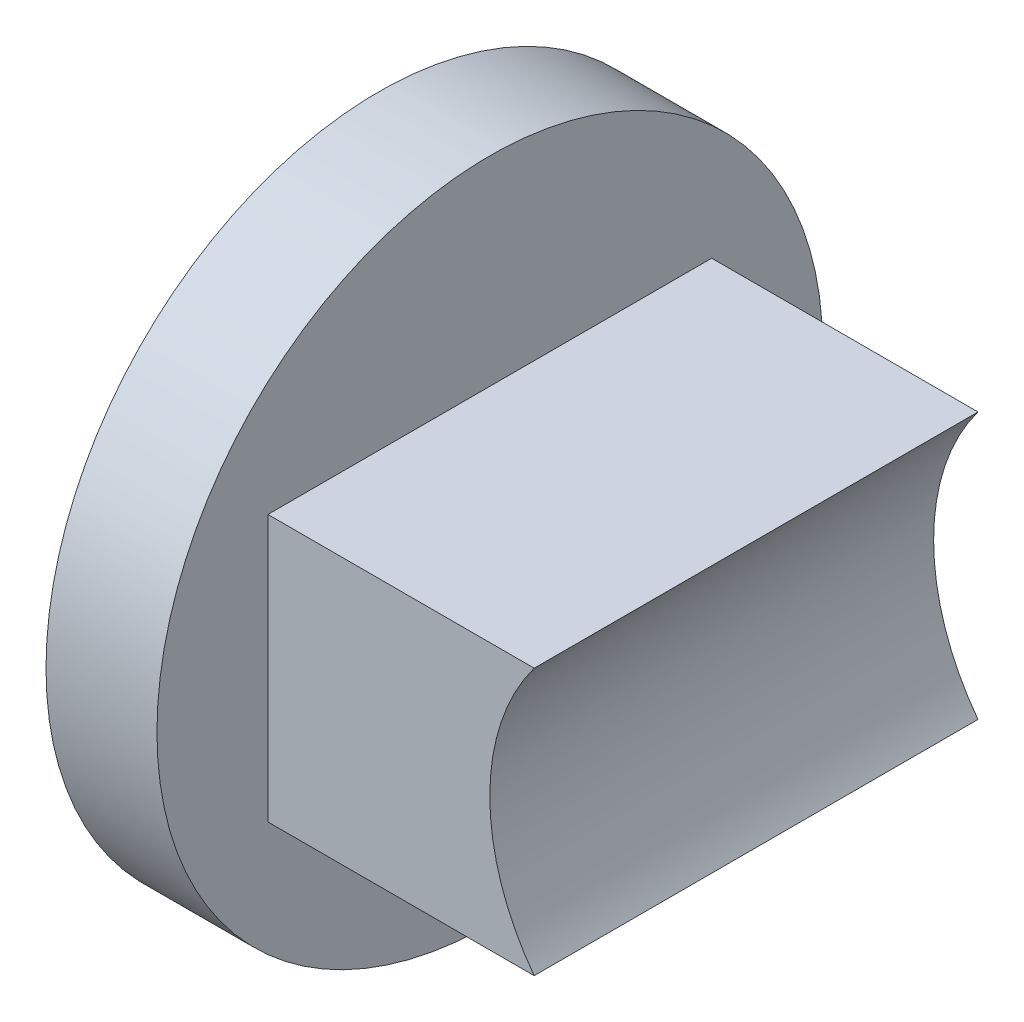
SolidWorks part; units mm, degrees
ref_plane "Front" through (0, 0, 0) normal (0, 0, 1) x (1, 0, 0)
ref_plane "Top" through (0, 0, 0) normal (0, 1, 0) x (1, 0, 0)
ref_plane "Right" through (0, 0, 0) normal (1, 0, 0) x (0, 0, -1)
sketch "草图1" plane through (0, 0, 0) normal (1, 0, 0) x (0, 0, -1)
  circle A1 centre (0, 0) radius 5
  circle A2 centre (0, 0) radius 30
extrude "凸台-拉伸1" add sketch "草图1" along normal blind 10
sketch "草图3" plane through (10, 0, 0) normal (1, 0, 0) x (0, 0, -1)
  line L0 (0, 0) -> (0, 40.3701) construction
  line L1 (-20, 12) -> (20, 12)
  line L2 (-20, 12) -> (-20, -12)
  line L3 (-20, -12) -> (20, -12)
  line L4 (20, 12) -> (20, -12)
  line L5 (0, 0) -> (39.5999, 0) construction
  dimension "D1" = 24
  dimension "D2" = 12
  dimension "D3" = 40
  dimension "D4" = 20
extrude "凸台-拉伸2" add sketch "草图3" along normal blind 30
sketch "草图4" plane through (0, 0, -20) normal (0, 0, -1) x (-1, 0, 0)
  line L0 (-40, 0) -> (-74.7532, 0) construction
  line L1 (-40, -12) -> (-40, 12) construction
  line L2 (-40, 12) -> (-40, -12) construction
  circle A0 centre (-50, 0) radius 20
  dimension "D1" = 10
extrude "切除-拉伸2" cut sketch "草图4" against normal through all
